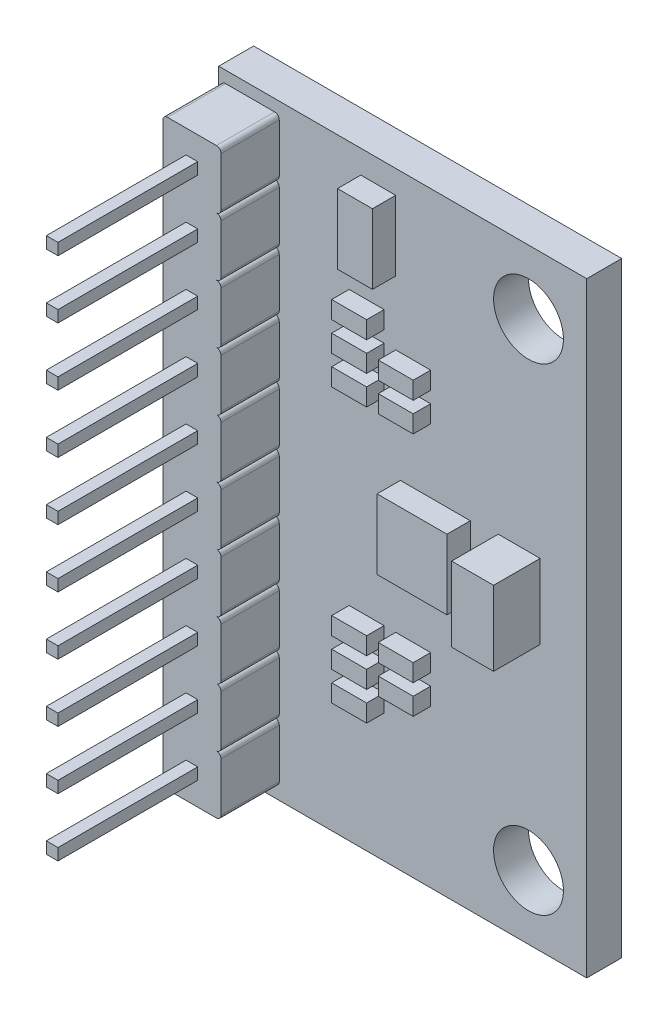
SolidWorks part; units mm, degrees
ref_plane "Front Plane" through (0, 0, 0) normal (0, 0, 1) x (1, 0, 0)
ref_plane "Top Plane" through (0, 0, 0) normal (0, 1, 0) x (1, 0, 0)
ref_plane "Right Plane" through (0, 0, 0) normal (1, 0, 0) x (0, 0, -1)
sketch "Sketch1" plane through (0, 0, 0) normal (0, 0, 1) x (1, 0, 0)
  line L0 (5.4, -10.25) -> (5.4, 10.25) construction
  line L1 (-7.9, -13) -> (7.9, -13)
  line L2 (-7.9, -13) -> (-7.9, 13)
  line L3 (-7.9, 13) -> (7.9, 13)
  line L4 (7.9, -13) -> (7.9, 13)
  circle A0 centre (5.4, 10.25) radius 1.5
  circle A1 centre (5.4, -10.25) radius 1.5
  dimension "D8" = 3
  dimension "D9" = 3
  dimension "D1" = 26
  dimension "D2" = 13
  dimension "D3" = 15.8
  dimension "D4" = 7.9
  dimension "D5" = 20.5
  dimension "D6" = 2.75
  dimension "D7" = 2.5
extrude "Boss-Extrude1" add sketch "Sketch1" along normal blind 1.5
sketch "Sketch2" plane through (0, 0, 1.5) normal (0, 0, 1) x (1, 0, 0)
  line L0 (-7.9, 13) -> (-7.9, -13) construction
  line L2 (-7.8, 10.2) -> (-7.8, 12.3)
  line L3 (-7.6, 12.5) -> (-5.5, 12.5)
  line L4 (-5.3, 10.2) -> (-5.3, 12.3)
  line L5 (-7.8, 7.7) -> (-7.8, 9.8)
  line L7 (-5.3, 7.7) -> (-5.3, 9.8)
  line L9 (-7.8, 5.2) -> (-7.8, 7.3)
  line L11 (-5.3, 5.2) -> (-5.3, 7.3)
  line L13 (-7.8, 2.7) -> (-7.8, 4.8)
  line L15 (-5.3, 2.7) -> (-5.3, 4.8)
  line L17 (-7.8, 0.2) -> (-7.8, 2.3)
  line L19 (-5.3, 0.2) -> (-5.3, 2.3)
  line L21 (-7.8, -2.3) -> (-7.8, -0.2)
  line L23 (-5.3, -2.3) -> (-5.3, -0.2)
  line L25 (-7.8, -4.8) -> (-7.8, -2.7)
  line L27 (-5.3, -4.8) -> (-5.3, -2.7)
  line L29 (-7.8, -7.3) -> (-7.8, -5.2)
  line L31 (-5.3, -7.3) -> (-5.3, -5.2)
  line L33 (-7.8, -9.8) -> (-7.8, -7.7)
  line L35 (-5.3, -9.8) -> (-5.3, -7.7)
  line L37 (-7.8, -12.3) -> (-7.8, -10.2)
  line L38 (-7.6, -12.5) -> (-5.5, -12.5)
  line L39 (-5.3, -12.3) -> (-5.3, -10.2)
  line L42 (7.9, 13) -> (-7.9, 13) construction
  line L44 (-7.6, 10) -> (-5.5, 10) [skipped]
  line L45 (-7.6, 7.5) -> (-5.5, 7.5) [skipped]
  line L46 (-7.6, 5) -> (-5.5, 5) [skipped]
  line L47 (-7.6, 2.5) -> (-5.5, 2.5) [skipped]
  line L48 (-7.6, 0) -> (-5.5, 0) [skipped]
  line L49 (-7.6, -2.5) -> (-5.5, -2.5) [skipped]
  line L50 (-7.6, -5) -> (-5.5, -5) [skipped]
  line L51 (-7.6, -7.5) -> (-5.5, -7.5) [skipped]
  line L52 (-7.6, -10) -> (-5.5, -10) [skipped]
  arc A0 (-7.8, 12.3) -> (-7.6, 12.5) centre (-7.6, 12.3) cw
  arc A1 (-5.5, 12.5) -> (-5.3, 12.3) centre (-5.5, 12.3) cw
  arc A2 (-5.5, 10) -> (-5.3, 10.2) centre (-5.5, 10.2) ccw
  arc A3 (-7.6, 10) -> (-7.8, 10.2) centre (-7.6, 10.2) cw
  arc A4 (-7.6, 7.5) -> (-7.8, 7.7) centre (-7.6, 7.7) cw
  arc A5 (-7.8, 9.8) -> (-7.6, 10) centre (-7.6, 9.8) cw
  arc A6 (-5.5, 7.5) -> (-5.3, 7.7) centre (-5.5, 7.7) ccw
  arc A7 (-5.5, 10) -> (-5.3, 9.8) centre (-5.5, 9.8) cw
  arc A8 (-7.6, 5) -> (-7.8, 5.2) centre (-7.6, 5.2) cw
  arc A9 (-7.8, 7.3) -> (-7.6, 7.5) centre (-7.6, 7.3) cw
  arc A10 (-5.5, 5) -> (-5.3, 5.2) centre (-5.5, 5.2) ccw
  arc A11 (-5.5, 7.5) -> (-5.3, 7.3) centre (-5.5, 7.3) cw
  arc A12 (-7.6, 2.5) -> (-7.8, 2.7) centre (-7.6, 2.7) cw
  arc A13 (-7.8, 4.8) -> (-7.6, 5) centre (-7.6, 4.8) cw
  arc A14 (-5.5, 2.5) -> (-5.3, 2.7) centre (-5.5, 2.7) ccw
  arc A15 (-5.5, 5) -> (-5.3, 4.8) centre (-5.5, 4.8) cw
  arc A16 (-7.6, 0) -> (-7.8, 0.2) centre (-7.6, 0.2) cw
  arc A17 (-7.8, 2.3) -> (-7.6, 2.5) centre (-7.6, 2.3) cw
  arc A18 (-5.5, 0) -> (-5.3, 0.2) centre (-5.5, 0.2) ccw
  arc A19 (-5.5, 2.5) -> (-5.3, 2.3) centre (-5.5, 2.3) cw
  arc A20 (-7.6, -2.5) -> (-7.8, -2.3) centre (-7.6, -2.3) cw
  arc A21 (-7.8, -0.2) -> (-7.6, 0) centre (-7.6, -0.2) cw
  arc A22 (-5.5, -2.5) -> (-5.3, -2.3) centre (-5.5, -2.3) ccw
  arc A23 (-5.5, 0) -> (-5.3, -0.2) centre (-5.5, -0.2) cw
  arc A24 (-7.6, -5) -> (-7.8, -4.8) centre (-7.6, -4.8) cw
  arc A25 (-7.8, -2.7) -> (-7.6, -2.5) centre (-7.6, -2.7) cw
  arc A26 (-5.5, -5) -> (-5.3, -4.8) centre (-5.5, -4.8) ccw
  arc A27 (-5.5, -2.5) -> (-5.3, -2.7) centre (-5.5, -2.7) cw
  arc A28 (-7.6, -7.5) -> (-7.8, -7.3) centre (-7.6, -7.3) cw
  arc A29 (-7.8, -5.2) -> (-7.6, -5) centre (-7.6, -5.2) cw
  arc A30 (-5.5, -7.5) -> (-5.3, -7.3) centre (-5.5, -7.3) ccw
  arc A31 (-5.5, -5) -> (-5.3, -5.2) centre (-5.5, -5.2) cw
  arc A32 (-7.6, -10) -> (-7.8, -9.8) centre (-7.6, -9.8) cw
  arc A33 (-7.8, -7.7) -> (-7.6, -7.5) centre (-7.6, -7.7) cw
  arc A34 (-5.5, -10) -> (-5.3, -9.8) centre (-5.5, -9.8) ccw
  arc A35 (-5.5, -7.5) -> (-5.3, -7.7) centre (-5.5, -7.7) cw
  arc A36 (-7.6, -12.5) -> (-7.8, -12.3) centre (-7.6, -12.3) cw
  arc A37 (-7.8, -10.2) -> (-7.6, -10) centre (-7.6, -10.2) cw
  arc A38 (-5.5, -12.5) -> (-5.3, -12.3) centre (-5.5, -12.3) ccw
  arc A39 (-5.5, -10) -> (-5.3, -10.2) centre (-5.5, -10.2) cw
  point P6 (-7.8, 12.5)
  point P9 (-5.3, 12.5)
  point P14 (-7.8, 10)
  dimension "D3" = 0.2
  dimension "D1" = 2.5
  dimension "D2" = 2.5
  dimension "D4" = 0.1
  dimension "D6" = 0.5
  dimension "D5" = 10
extrude "Boss-Extrude2" add sketch "Sketch2" along normal blind 2.5
sketch "Sketch3" plane through (0, 0, 4) normal (0, 0, 1) x (1, 0, 0)
  line L0 (-7.8, 12.3) -> (-7.8, 10.2) construction
  line L1 (-6.8, 11) -> (-6.3, 11)
  line L2 (-6.8, 11) -> (-6.8, 11.5)
  line L3 (-6.8, 11.5) -> (-6.3, 11.5)
  line L4 (-6.3, 11) -> (-6.3, 11.5)
  line L5 (-5.5, 12.5) -> (-7.6, 12.5) construction
  line L6 (-6.8, 8.5) -> (-6.8, 9)
  line L7 (-6.8, 8.5) -> (-6.3, 8.5)
  line L8 (-6.3, 8.5) -> (-6.3, 9)
  line L9 (-6.8, 9) -> (-6.3, 9)
  line L10 (-6.8, 6) -> (-6.8, 6.5)
  line L11 (-6.8, 6) -> (-6.3, 6)
  line L12 (-6.3, 6) -> (-6.3, 6.5)
  line L13 (-6.8, 6.5) -> (-6.3, 6.5)
  line L14 (-6.8, 3.5) -> (-6.8, 4)
  line L15 (-6.8, 3.5) -> (-6.3, 3.5)
  line L16 (-6.3, 3.5) -> (-6.3, 4)
  line L17 (-6.8, 4) -> (-6.3, 4)
  line L18 (-6.8, 1) -> (-6.8, 1.5)
  line L19 (-6.8, 1) -> (-6.3, 1)
  line L20 (-6.3, 1) -> (-6.3, 1.5)
  line L21 (-6.8, 1.5) -> (-6.3, 1.5)
  line L22 (-6.8, -1.5) -> (-6.8, -1)
  line L23 (-6.8, -1.5) -> (-6.3, -1.5)
  line L24 (-6.3, -1.5) -> (-6.3, -1)
  line L25 (-6.8, -1) -> (-6.3, -1)
  line L26 (-6.8, -4) -> (-6.8, -3.5)
  line L27 (-6.8, -4) -> (-6.3, -4)
  line L28 (-6.3, -4) -> (-6.3, -3.5)
  line L29 (-6.8, -3.5) -> (-6.3, -3.5)
  line L30 (-6.8, -6.5) -> (-6.8, -6)
  line L31 (-6.8, -6.5) -> (-6.3, -6.5)
  line L32 (-6.3, -6.5) -> (-6.3, -6)
  line L33 (-6.8, -6) -> (-6.3, -6)
  line L34 (-6.8, -9) -> (-6.8, -8.5)
  line L35 (-6.8, -9) -> (-6.3, -9)
  line L36 (-6.3, -9) -> (-6.3, -8.5)
  line L37 (-6.8, -8.5) -> (-6.3, -8.5)
  line L38 (-6.8, -11.5) -> (-6.8, -11)
  line L39 (-6.8, -11.5) -> (-6.3, -11.5)
  line L40 (-6.3, -11.5) -> (-6.3, -11)
  line L41 (-6.8, -11) -> (-6.3, -11)
  dimension "D1" = 0.5
  dimension "D2" = 0.5
  dimension "D3" = 1
  dimension "D4" = 1
  dimension "D5" = 10
extrude "Boss-Extrude3" add sketch "Sketch3" along normal blind 6 and the other way blind 5
sketch "Sketch4" plane through (0, 0, 1.5) normal (0, 0, 1) x (1, 0, 0)
  line L0 (-5.3, 10.2) -> (-5.3, 12.3) construction
  line L1 (-0.1, -1.5) -> (2.9, -1.5)
  line L2 (-0.1, -1.5) -> (-0.1, 1.5)
  line L3 (-0.1, 1.5) -> (2.9, 1.5)
  line L4 (2.9, -1.5) -> (2.9, 1.5)
  line L5 (-1.8, 9) -> (-0.3, 9)
  line L6 (-1.8, 9) -> (-1.8, 12)
  line L7 (-1.8, 12) -> (-0.3, 12)
  line L8 (-0.3, 9) -> (-0.3, 12)
  line L9 (7.9, 13) -> (-7.9, 13) construction
  line L10 (-7.9, -13) -> (7.9, -13) construction
  line L11 (7.9, -13) -> (7.9, 13) construction
  dimension "D1" = 3
  dimension "D2" = 1.5
  dimension "D3" = 3.5
  dimension "D4" = 1
  dimension "D5" = 3
  dimension "D6" = 3
  dimension "D7" = 11.5
  dimension "D8" = 5
extrude "Boss-Extrude4" add sketch "Sketch4" along normal blind 1
sketch "Sketch5" plane through (0, 0, 1.5) normal (0, 0, 1) x (1, 0, 0)
  line L1 (4.1, -1.6) -> (5.9, -1.6)
  line L2 (4.1, -1.6) -> (4.1, 1.6)
  line L3 (4.1, 1.6) -> (5.9, 1.6)
  line L4 (5.9, -1.6) -> (5.9, 1.6)
  line L5 (-0.1, -1.5) -> (2.9, -1.5) construction
  line L6 (7.9, -13) -> (7.9, 13) construction
  point P8 (7.9, 0)
  dimension "D1" = 3.2
  dimension "D2" = 0.1
  dimension "D3" = 1.8
  dimension "D4" = 2
extrude "Boss-Extrude5" add sketch "Sketch5" along normal blind 2
sketch "Sketch6" plane through (0, 0, 1.5) normal (0, 0, 1) x (1, 0, 0)
  line L0 (-5.3, 7.7) -> (-5.3, 9.8) construction
  line L1 (-2.3, 6.75) -> (-0.8, 6.75)
  line L2 (-2.3, 6.75) -> (-2.3, 7.5)
  line L3 (-2.3, 7.5) -> (-0.8, 7.5)
  line L4 (-0.8, 6.75) -> (-0.8, 7.5)
  line L5 (-1.8, 9) -> (-0.3, 9) construction
  line L6 (-2.3, 5.5) -> (-2.3, 6.25)
  line L7 (-2.3, 5.5) -> (-0.8, 5.5)
  line L8 (-0.8, 5.5) -> (-0.8, 6.25)
  line L9 (-2.3, 6.25) -> (-0.8, 6.25)
  line L10 (-2.3, 4.25) -> (-2.3, 5)
  line L11 (-2.3, 4.25) -> (-0.8, 4.25)
  line L12 (-0.8, 4.25) -> (-0.8, 5)
  line L13 (-2.3, 5) -> (-0.8, 5)
  line L14 (-0.3, 5.5) -> (-0.3, 6.25)
  line L15 (-0.3, 5.5) -> (1.2, 5.5)
  line L16 (1.2, 5.5) -> (1.2, 6.25)
  line L17 (-0.3, 6.25) -> (1.2, 6.25)
  line L18 (-0.3, 4.25) -> (-0.3, 5)
  line L19 (-0.3, 4.25) -> (1.2, 4.25)
  line L20 (1.2, 4.25) -> (1.2, 5)
  line L21 (-0.3, 5) -> (1.2, 5)
  line L26 (-1000, 0) -> (49000, 0) construction
  line L27 (-0.3, 6.75) -> (-0.3, 7.5) [skipped]
  line L28 (-0.3, 7.5) -> (1.2, 7.5) [skipped]
  line L29 (1.2, 6.75) -> (1.2, 7.5) [skipped]
  line L30 (-0.3, 6.75) -> (1.2, 6.75) [skipped]
  line L31 (-0.3, -5) -> (1.2, -5)
  line L32 (1.2, -4.25) -> (1.2, -5)
  line L33 (-0.3, -4.25) -> (1.2, -4.25)
  line L34 (-0.3, -4.25) -> (-0.3, -5)
  line L35 (-0.3, -6.25) -> (1.2, -6.25)
  line L36 (1.2, -5.5) -> (1.2, -6.25)
  line L37 (-0.3, -5.5) -> (1.2, -5.5)
  line L38 (-0.3, -5.5) -> (-0.3, -6.25)
  line L39 (-2.3, -5) -> (-0.8, -5)
  line L40 (-0.8, -4.25) -> (-0.8, -5)
  line L41 (-2.3, -4.25) -> (-0.8, -4.25)
  line L42 (-2.3, -4.25) -> (-2.3, -5)
  line L43 (-2.3, -6.25) -> (-0.8, -6.25)
  line L44 (-0.8, -5.5) -> (-0.8, -6.25)
  line L45 (-2.3, -5.5) -> (-0.8, -5.5)
  line L46 (-2.3, -5.5) -> (-2.3, -6.25)
  line L47 (-0.8, -6.75) -> (-0.8, -7.5)
  line L48 (-2.3, -7.5) -> (-0.8, -7.5)
  line L49 (-2.3, -6.75) -> (-2.3, -7.5)
  line L50 (-2.3, -6.75) -> (-0.8, -6.75)
  point P8 (-1.05, 9)
  dimension "D1" = 0.75
  dimension "D2" = 1.5
  dimension "D3" = 3
  dimension "D4" = 1.5
  dimension "D5" = 3
  dimension "D6" = 2
extrude "Boss-Extrude6" add sketch "Sketch6" along normal blind 0.75
